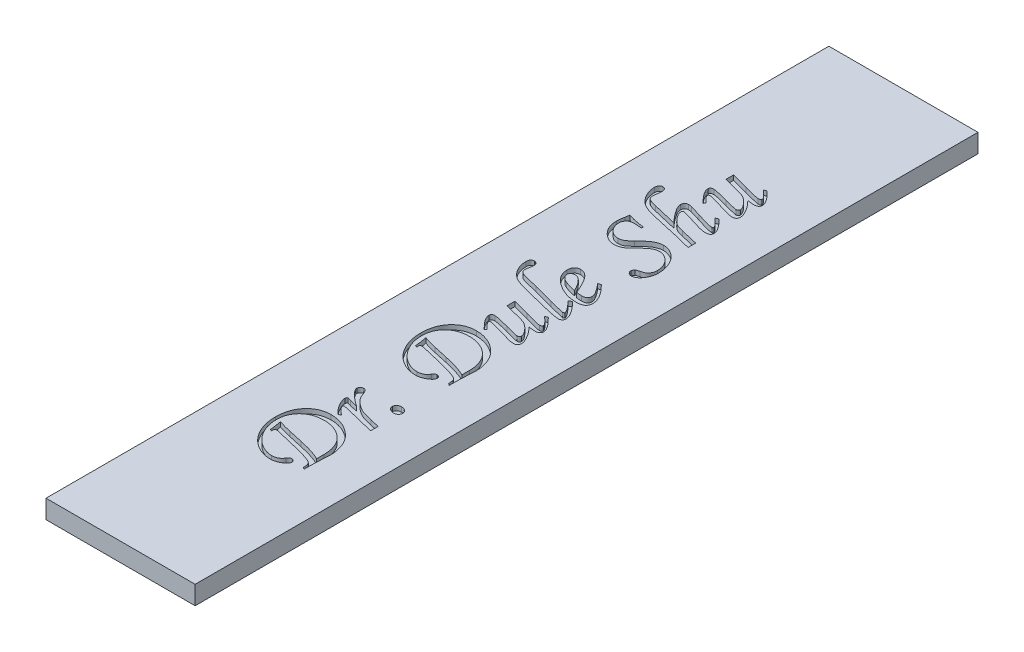
SolidWorks part; units mm, degrees
ref_plane "Front Plane" through (0, 0, 0) normal (0, 0, 1) x (1, 0, 0)
ref_plane "Top Plane" through (0, 0, 0) normal (0, 1, 0) x (1, 0, 0)
ref_plane "Right Plane" through (0, 0, 0) normal (1, 0, 0) x (0, 0, -1)
sketch "Sketch1" plane through (0, 0, 0) normal (0, 0, 1) x (1, 0, 0)
  line L0 (0, 1.5875) -> (0, -1.5875)
  line L1 (-12.7, 0) -> (12.7, 0) construction
  point P6 (0, 0)
  dimension "Width" = 25.4
  dimension "Thk" = 3.175
sketch "Sketch2" plane through (0, 0, 0) normal (1, 0, 0) x (0, 0, -1)
  line L0 (66.675, 0) -> (-66.675, 0)
  point P4 (0, 0)
  dimension "Length" = 133.35
sketch "Sketch3" plane through (0, 0, 0) normal (0, 0, 1) x (1, 0, 0)
  line L1 (12.7, 1.5875) -> (-12.7, 1.5875)
  line L2 (12.7, 1.5875) -> (12.7, -1.5875)
  line L3 (12.7, -1.5875) -> (-12.7, -1.5875)
  line L4 (-12.7, 1.5875) -> (-12.7, -1.5875)
  line L5 (12.7, 1.5875) -> (-12.7, -1.5875) construction
  line L6 (12.7, -1.5875) -> (-12.7, 1.5875) construction
  point P0 (0, 0)
extrude "Boss-Extrude1" add sketch "Sketch3" along normal up to vertex (66.675 mm away) and the other way up to vertex (66.675 mm away) up to point (0, 0, 66.675) other way up to point (0, 0, -66.675)
sketch "Sketch4" plane through (0, 1.5875, 0) normal (0, 1, 0) x (1, 0, 0)
  line L0 (0, 0) -> (5, 0) construction
  line L1 (5, -66.675) -> (5, 66.675) construction
  line L2 (12.7, -66.675) -> (-12.7, -66.675) construction
  text T0 "Dr. Dule Shu " font "Monotype Corsiva" height 10
  point P6 (5, 0)
  point P7 (7.5296, -66.675)
  dimension "D1" = 5
extrude "Cut-Extrude1" cut sketch "Sketch4" against normal blind 0.7937
